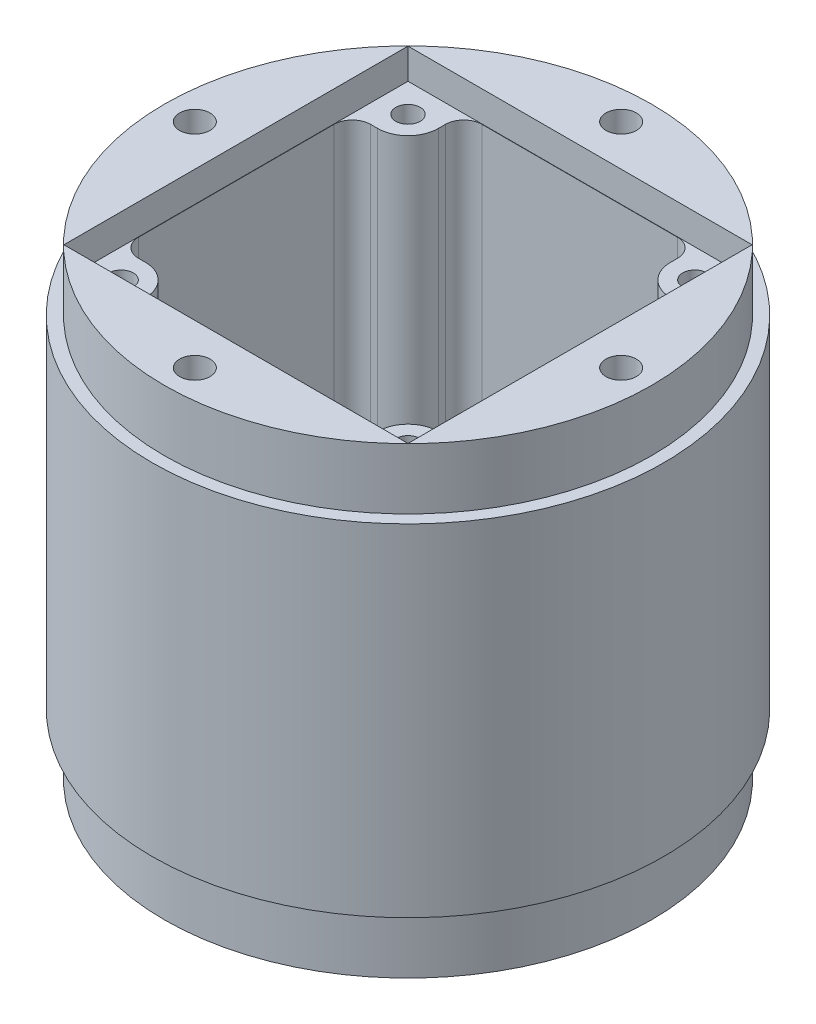
SolidWorks part; units mm, degrees
ref_plane "Front Plane" through (0, 0, 0) normal (0, 0, 1) x (1, 0, 0)
ref_plane "Top Plane" through (0, 0, 0) normal (0, 1, 0) x (1, 0, 0)
ref_plane "Right Plane" through (0, 0, 0) normal (1, 0, 0) x (0, 0, -1)
sketch "Sketch2" plane through (0, 0, 0) normal (0, 1, 0) x (1, 0, 0)
  line L7 (-16.05, 28.2) -> (16.05, 28.2)
  line L8 (-28.2, 16.05) -> (-28.2, -16.05)
  line L9 (-16.05, -28.2) -> (16.05, -28.2)
  line L10 (28.2, 16.05) -> (28.2, -16.05)
  line L15 (-25.2, 19.05) -> (-24.05, 19.05)
  line L16 (-19.05, 25.2) -> (-19.05, 24.05)
  line L19 (25.2, 19.05) -> (24.05, 19.05)
  line L20 (19.05, 25.2) -> (19.05, 24.05)
  line L21 (-24.05, -19.05) -> (-25.2, -19.05)
  line L22 (-19.05, -24.05) -> (-19.05, -25.2)
  line L25 (24.05, -19.05) -> (25.2, -19.05)
  line L26 (19.05, -24.05) -> (19.05, -25.2)
  circle A0 centre (0, 0) radius 40
  arc A1 (24.05, 19.05) -> (19.05, 24.05) centre (24.05, 24.05) cw
  arc A2 (-24.05, 19.05) -> (-19.05, 24.05) centre (-24.05, 24.05) ccw
  arc A3 (-24.05, -19.05) -> (-19.05, -24.05) centre (-24.05, -24.05) cw
  arc A4 (19.05, -24.05) -> (24.05, -19.05) centre (24.05, -24.05) cw
  arc A5 (-28.2, 16.05) -> (-25.2, 19.05) centre (-25.2, 16.05) cw
  arc A6 (-28.2, -16.05) -> (-25.2, -19.05) centre (-25.2, -16.05) ccw
  arc A7 (-16.05, -28.2) -> (-19.05, -25.2) centre (-16.05, -25.2) cw
  arc A8 (16.05, -28.2) -> (19.05, -25.2) centre (16.05, -25.2) ccw
  arc A9 (25.2, -19.05) -> (28.2, -16.05) centre (25.2, -16.05) ccw
  arc A10 (28.2, 16.05) -> (25.2, 19.05) centre (25.2, 16.05) ccw
  arc A11 (16.05, 28.2) -> (19.05, 25.2) centre (16.05, 25.2) cw
  arc A12 (-19.05, 25.2) -> (-16.05, 28.2) centre (-16.05, 25.2) cw
  point P0 (0, 0)
  point P6 (0, 0)
  point P11 (19.05, 19.05)
  point P24 (-19.05, -19.05)
  point P27 (19.05, -19.05)
  point P40 (28.2, 19.05)
  point P43 (19.05, 28.2)
  point P46 (-19.05, 28.2)
  dimension "D7" = 80
  dimension "D8" = 5
  dimension "D9" = 3
  dimension "D1" = 38.1
  dimension "D2" = 38.1
  dimension "D3" = 9.15
  dimension "D4" = 38.1
  dimension "D5" = 9.15
  dimension "D6" = 28.2
extrude "Boss-Extrude1" add sketch "Sketch2" along normal blind 76
sketch "Sketch3" plane through (0, 0, 28.2) normal (0, 0, -1) x (-1, 0, 0)
  line L0 (16.05, 0) -> (-16.05, 0) construction
  line L1 (-4, 20) -> (4, 20)
  line L2 (-4, 20) -> (-4, 0)
  line L3 (-4, 0) -> (4, 0)
  line L4 (4, 20) -> (4, 0)
  point P6 (0, 0)
  dimension "D1" = 8
  dimension "D2" = 20
extrude "Cut-Extrude1" cut sketch "Sketch3" against normal blind 3
ref_plane "Plane1" through (0, 38, 0) normal (0, 1, 0) x (1, 0, 0)
sketch "Sketch4" plane through (0, 38, 0) normal (0, 1, 0) x (1, 0, 0)
  circle A0 centre (0, 0) radius 42
  circle A1 centre (0, 0) radius 40
  dimension "D1" = 84
extrude "Boss-Extrude3" add sketch "Sketch4" along normal mid plane 56
sketch "Sketch5" plane through (0, 76, 0) normal (0, 1, 0) x (1, 0, 0)
  line L1 (-28.25, 28.25) -> (28.25, 28.25)
  line L2 (-28.25, 28.25) -> (-28.25, -28.25)
  line L3 (-28.25, -28.25) -> (28.25, -28.25)
  line L4 (28.25, 28.25) -> (28.25, -28.25)
  line L5 (-28.25, 28.25) -> (28.25, -28.25) construction
  line L6 (-28.25, -28.25) -> (28.25, 28.25) construction
  point P0 (0, 0)
  dimension "D1" = 56.5
extrude "Cut-Extrude7" cut sketch "Sketch5" against normal blind 5
sketch "Sketch6" plane through (0, 71, 0) normal (0, 1, 0) x (1, 0, 0)
  line L1 (-23.55, 23.55) -> (23.55, 23.55)
  line L2 (-23.55, 23.55) -> (-23.55, -23.55)
  line L3 (-23.55, -23.55) -> (23.55, -23.55)
  line L4 (23.55, 23.55) -> (23.55, -23.55)
  line L5 (-23.55, 23.55) -> (23.55, -23.55) construction
  line L6 (-23.55, -23.55) -> (23.55, 23.55) construction
  circle A0 centre (-23.55, 23.55) radius 2
  circle A1 centre (23.55, 23.55) radius 2
  circle A2 centre (23.55, -23.55) radius 2
  circle A3 centre (-23.55, -23.55) radius 2
  point P0 (0, 0)
  dimension "D3" = 4
  dimension "D1" = 47.1
  dimension "D2" = 47.1
extrude "Cut-Extrude8" cut sketch "Sketch6" against normal through all contours A0 | A1 | A3 | A2
sketch "Sketch7" plane through (0, 76, 0) normal (0, 1, 0) x (1, 0, 0)
  circle A0 centre (0, 0) radius 35
  circle A1 centre (0, 35) radius 2.5
  circle A2 centre (35, 0) radius 2.5
  circle A3 centre (0, -35) radius 2.5
  circle A4 centre (-35, 0) radius 2.5
  point P14 (0, 0)
  dimension "D1" = 70
  dimension "D2" = 5
  dimension "D3" = 4
extrude "Cut-Extrude9" cut sketch "Sketch7" against normal through all contours A4 | A1 | A2 | A3
